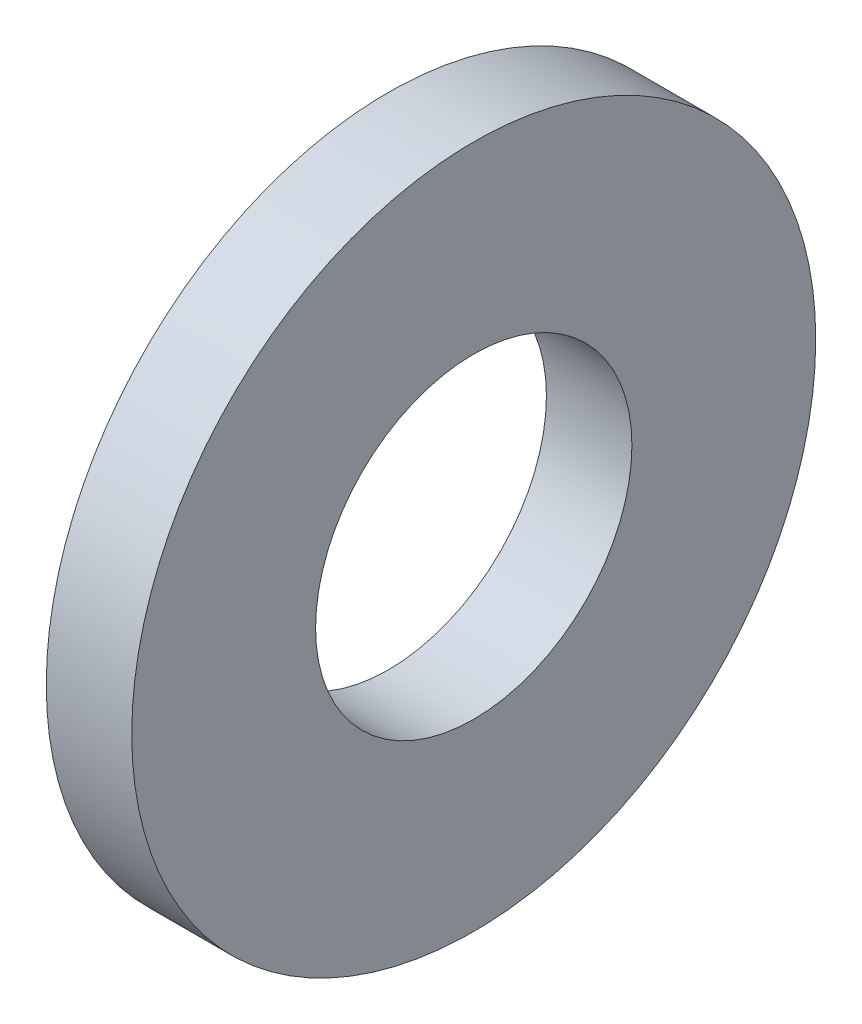
SolidWorks part; units mm, degrees
ref_plane "Plane1" through (0, 0, 0) normal (0, 0, 1) x (1, 0, 0)
ref_plane "Plane2" through (0, 0, 0) normal (0, 1, 0) x (1, 0, 0)
ref_plane "Plane3" through (0, 0, 0) normal (1, 0, 0) x (0, 0, -1)
other "Configuration Table"
sketch "Sketch1" plane through (0, 0, 0) normal (1, 0, 0) x (0, 0, -1)
  circle A0 centre (0, 0) radius 3.7
  circle A1 centre (0, 0) radius 8
  dimension "Insid_dia" = 7.4
  dimension "OutsideDia" = 16
extrude "Base-Extrude" add sketch "Sketch1" along normal blind 2
